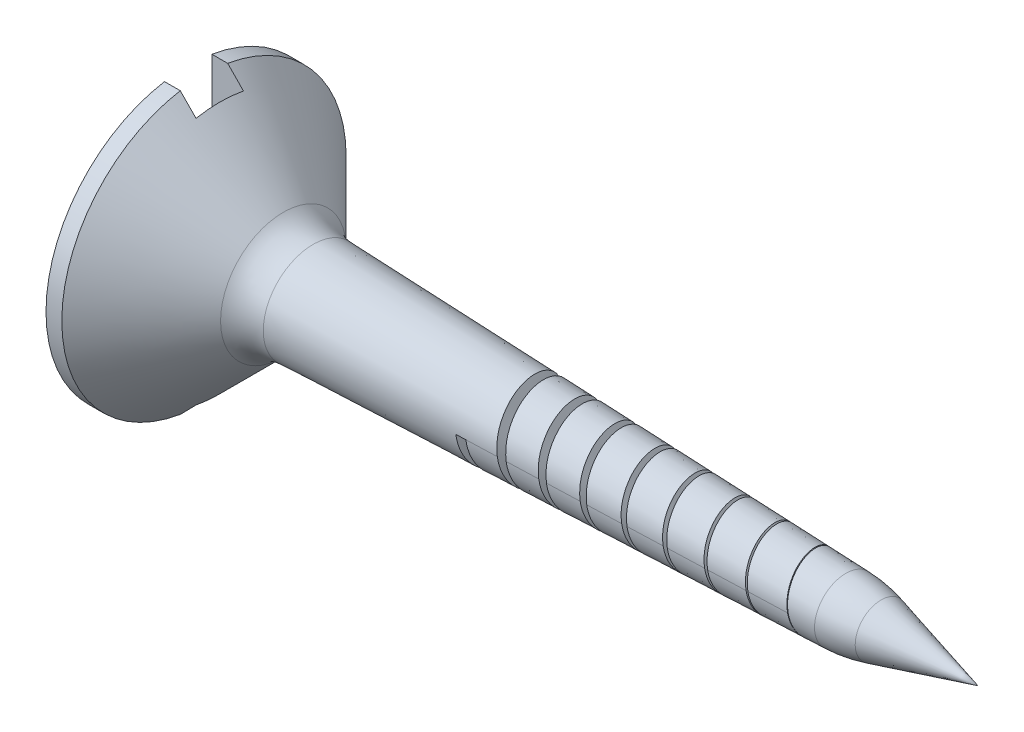
SolidWorks part; units mm, degrees
material "钛 Ti-8Mn，退火"
ref_plane "前视基准面" through (0, 0, 0) normal (0, 0, 1) x (1, 0, 0)
ref_plane "上视基准面" through (0, 0, 0) normal (0, 1, 0) x (1, 0, 0)
ref_plane "右视基准面" through (0, 0, 0) normal (1, 0, 0) x (0, 0, -1)
sketch "草图1" plane through (0, 0, 0) normal (0, 0, 1) x (1, 0, 0)
  line L0 (-23.2927, 0) -> (26.7073, 0)
  line L1 (-23.2927, 0) -> (-23.2927, 9)
  line L2 (-23.2927, 9) -> (-22.2927, 9)
  line L3 (-22.2927, 9) -> (-17.2673, 3.9746)
  line L4 (-15.3825, 3.155) -> (18.3368, 1.9775)
  line L5 (20.576, 1.6429) -> (26.7073, 0)
  arc A0 (-17.2673, 3.9746) -> (-15.3825, 3.155) centre (-15.2847, 5.9572) ccw
  arc A1 (18.3368, 1.9775) -> (20.576, 1.6429) centre (17.9878, -8.0164) cw
  point P11 (0, 0)
  point P12 (-15.2847, 3.155)
  point P13 (-22.39, 9)
  point P14 (-22.9562, 9)
  dimension "D3" = 10
  dimension "D1" = 50
  dimension "D2" = 45
  dimension "D4" = 15
  dimension "D5" = 2
  dimension "D6" = 9
  dimension "D7" = 1
revolve "旋转2" add sketch "草图1" angle 360 about L0
ref_plane "基准面1" through (-3.2927, 0, 0) normal (-1, 0, 0) x (0, 0, 1)
sketch "草图2" plane through (-3.2927, 0, 0) normal (-1, 0, 0) x (0, 0, 1)
  circle A0 centre (0, 0) radius 2
  dimension "D1" = 4
curve "螺旋线/涡状线1" pitch 2.5 height 30 turns 12
sketch "草图3" plane through (0, 0, 0) normal (0, 1, 0) x (1, 0, 0)
  line L0 (-3.2927, -1.9889) -> (-3.7832, -3.1732)
  line L1 (-3.7832, -3.1732) -> (-2.8022, -3.1732)
  line L2 (-2.8022, -3.1732) -> (-3.2927, -1.9889)
  line L3 (-3.2927, 9.9) -> (-3.2927, -9.9) construction
  point P2 (-2.6425, -3.1001)
  point P4 (-3.2927, -3.1732)
  point P7 (0, 0)
  point P10 (0, 0)
  dimension "D1" = 45
  dimension "D2" = 112.5
sweep "切除-扫描1" cut profiles "草图3" path "螺旋线/涡状线1"
sketch "草图4" plane through (0, 0, 0) normal (0, 1, 0) x (1, 0, 0)
  line L0 (-23.2927, 9) -> (-23.2927, -9) construction
  line L1 (-23.2927, 1.5) -> (-21.2927, 1.5)
  line L2 (-23.2927, 1.5) -> (-23.2927, -1.5)
  line L3 (-23.2927, -1.5) -> (-21.2927, -1.5)
  line L4 (-21.2927, 1.5) -> (-21.2927, -1.5)
  point P6 (-23.2927, 0)
  dimension "D1" = 3
  dimension "D2" = 2
extrude "切除-拉伸1" cut sketch "草图4" against normal mid plane 30
